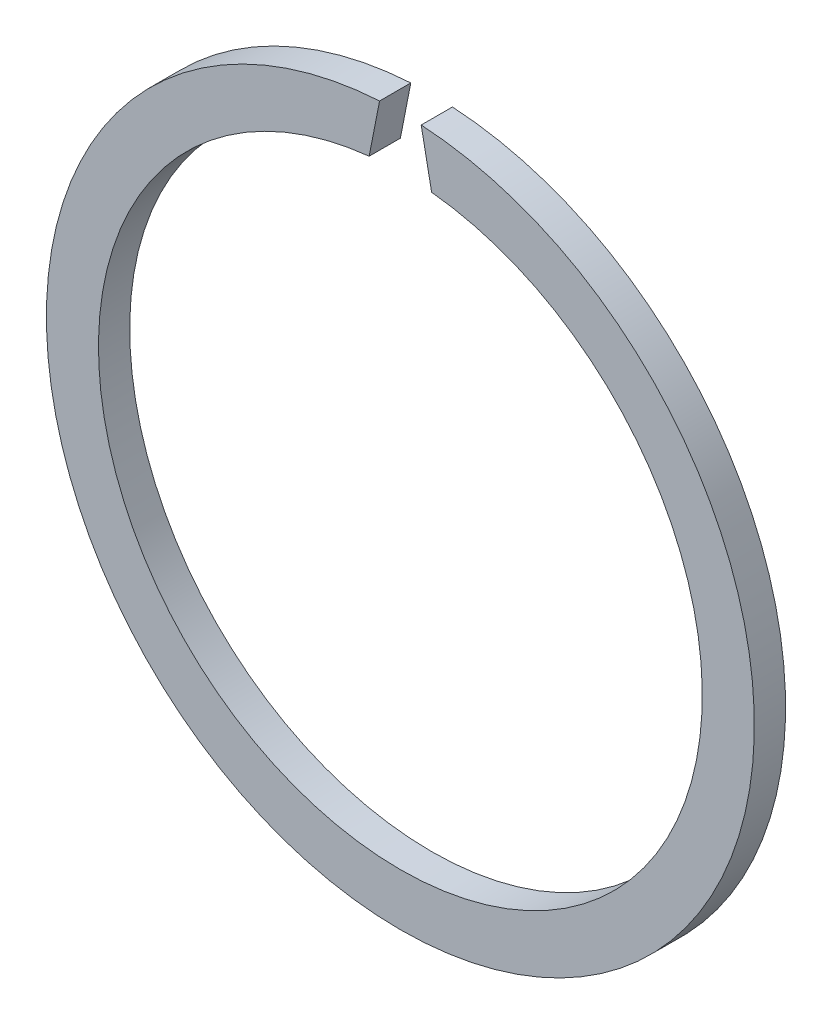
SolidWorks part; units mm, degrees
ref_plane "Front Plane" through (0, 0, 0) normal (0, 0, 1) x (1, 0, 0)
ref_plane "Top Plane" through (0, 0, 0) normal (0, 1, 0) x (1, 0, 0)
ref_plane "Right Plane" through (0, 0, 0) normal (1, 0, 0) x (0, 0, -1)
sketch "Sketch1" plane through (0, 0, 0) normal (0, 0, 1) x (1, 0, 0)
  line L0 (-1.5, 14.4222) -> (1.5, 14.4222) construction
  line L1 (-1, 16.9706) -> (1, 16.9706) construction
  line L2 (1, 16.9706) -> (0, 16.9706) construction
  line L3 (0, 16.9706) -> (0, 14.4222) construction
  line L4 (0, -55) -> (0, 55) construction
  line L5 (-1, 16.9706) -> (-1.5, 14.4222)
  line L6 (1.5, 14.4222) -> (1, 16.9706)
  arc A0 (-1.5, 14.4222) -> (1.5, 14.4222) centre (0, 0) ccw
  arc A1 (1, 16.9706) -> (-1, 16.9706) centre (0, 0) cw
  dimension "D1" = 14.5
  dimension "D2" = 17
  dimension "D3" = 2
  dimension "D4" = 3
extrude "Extrude1" add sketch "Sketch1" along normal blind 1.5
